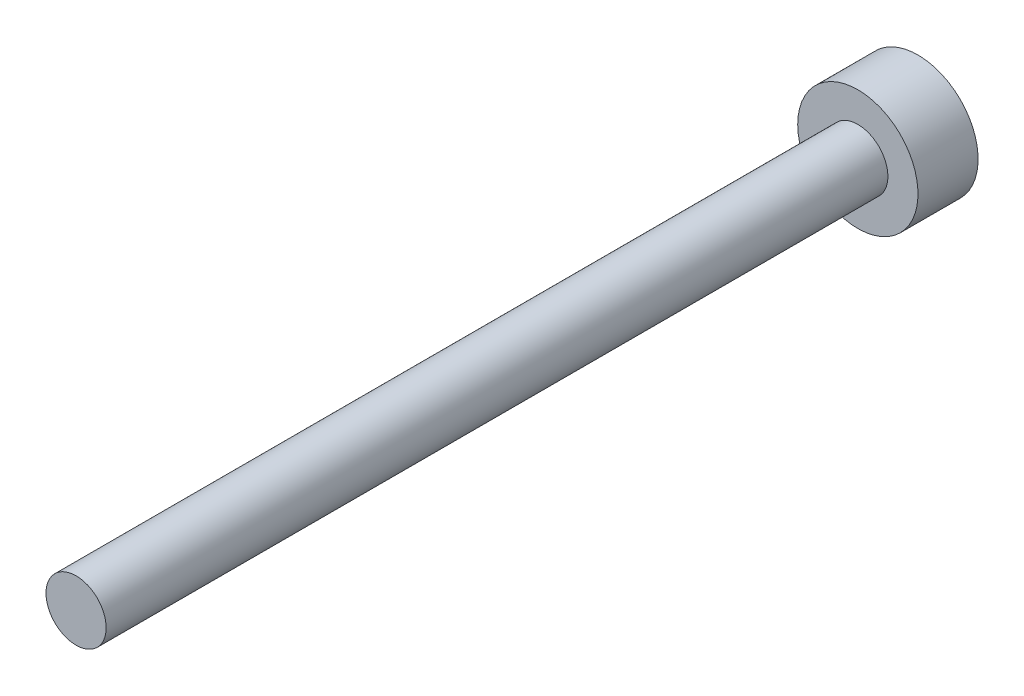
SolidWorks part; units mm, degrees
ref_plane "前视基准面" through (0, 0, 0) normal (0, 0, 1) x (1, 0, 0)
ref_plane "上视基准面" through (0, 0, 0) normal (0, 1, 0) x (1, 0, 0)
ref_plane "右视基准面" through (0, 0, 0) normal (1, 0, 0) x (0, 0, -1)
sketch "草图1" plane through (0, 0, 0) normal (0, 0, 1) x (1, 0, 0)
  circle A0 centre (0, 0) radius 2
extrude "凸台-拉伸1" add sketch "草图1" along normal blind 52
sketch "草图2" plane through (0, 0, 0) normal (0, 0, -1) x (-1, 0, 0)
  circle A0 centre (0, 0) radius 4
extrude "凸台-拉伸2" add sketch "草图2" along normal blind 4
sketch "草图3" plane through (0, 0, -4) normal (0, 0, -1) x (-1, 0, 0)
  line L1 (2, 0) -> (1, 1.7321)
  line L2 (1, 1.7321) -> (-1, 1.7321)
  line L3 (-1, 1.7321) -> (-2, 0)
  line L4 (-2, 0) -> (-1, -1.7321)
  line L5 (-1, -1.7321) -> (1, -1.7321)
  line L6 (1, -1.7321) -> (2, 0)
  circle A0 centre (0, 0) radius 2 construction
extrude "切除-拉伸1" cut sketch "草图3" against normal blind 2
